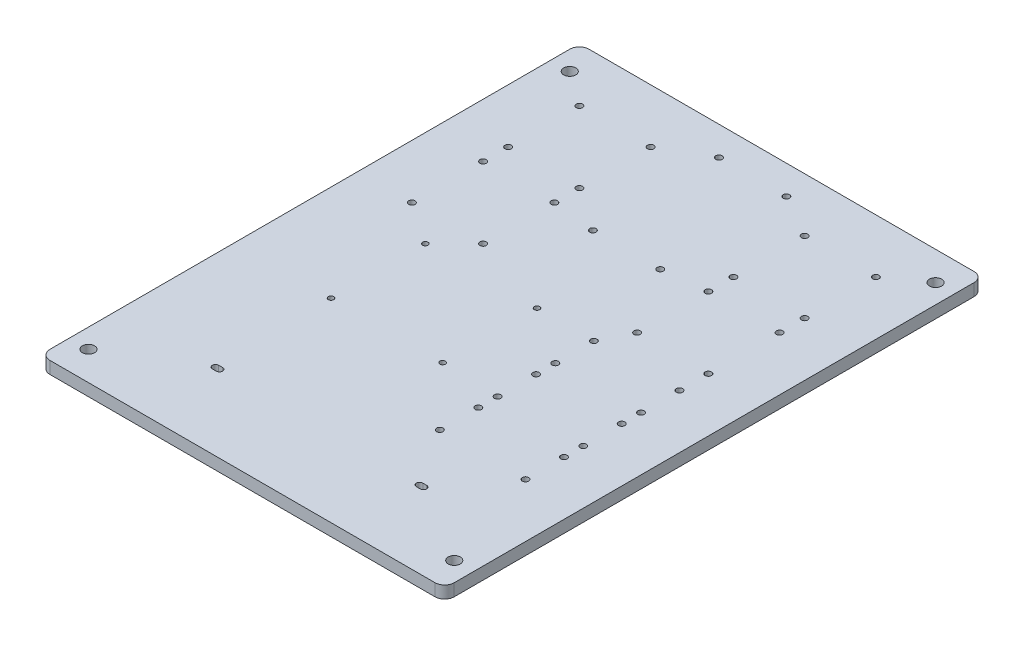
SolidWorks part; units mm, degrees
ref_plane "Front Plane" through (0, 0, 0) normal (0, 0, 1) x (1, 0, 0)
ref_plane "Top Plane" through (0, 0, 0) normal (0, 1, 0) x (1, 0, 0)
ref_plane "Right Plane" through (0, 0, 0) normal (1, 0, 0) x (0, 0, -1)
sketch "Sketch1" plane through (0, 0, 0) normal (0, 1, 0) x (1, 0, 0)
  line L1 (-105, -140) -> (105, -140)
  line L2 (-105, -140) -> (-105, 140)
  line L3 (-105, 140) -> (105, 140)
  line L4 (105, -140) -> (105, 140)
  line L5 (-105, -140) -> (105, 140) construction
  line L6 (-105, 140) -> (105, -140) construction
  point P0 (0, 0)
  dimension "D1" = 210
  dimension "D2" = 280
extrude "Boss-Extrude1" add sketch "Sketch1" against normal blind 6.35
sketch "Sketch2" plane through (0, 0, 0) normal (0, 1, 0) x (1, 0, 0)
  line L0 (-105, 140) -> (-105, -140) construction
  line L1 (95, -125) -> (-95, -125) construction
  line L2 (95, -125) -> (95, 125) construction
  line L3 (95, 125) -> (-95, 125) construction
  line L4 (-95, -125) -> (-95, 125) construction
  line L5 (95, -125) -> (-95, 125) construction
  line L6 (95, 125) -> (-95, -125) construction
  circle A0 centre (-95, 125) radius 3.15
  circle A1 centre (95, 125) radius 3.15
  circle A2 centre (-95, -125) radius 3.15
  circle A3 centre (95, -125) radius 3.15
  point P0 (0, 0)
  dimension "D1" = 6.3
  dimension "D2" = 10
  dimension "D3" = 250
extrude "Cut-Extrude1" cut sketch "Sketch2" against normal through all
sketch "Sketch3" plane through (0, 0, 0) normal (0, 1, 0) x (1, 0, 0)
  line L0 (0, 0) -> (0, -100) construction
  line L1 (0, -100) -> (53, -100) construction
  line L2 (0, -100) -> (-53, -100) construction
  line L3 (52, -100) -> (54, -100) construction
  line L4 (52, -98.35) -> (54, -98.35)
  line L5 (52, -101.65) -> (54, -101.65)
  line L6 (-54, -100) -> (-52, -100) construction
  line L7 (-54, -98.35) -> (-52, -98.35)
  line L8 (-54, -101.65) -> (-52, -101.65)
  line L9 (-105, -140) -> (105, -140) construction
  arc A0 (52, -98.35) -> (52, -101.65) centre (52, -100) ccw
  arc A1 (54, -101.65) -> (54, -98.35) centre (54, -100) ccw
  arc A2 (-54, -98.35) -> (-54, -101.65) centre (-54, -100) ccw
  arc A3 (-52, -101.65) -> (-52, -98.35) centre (-52, -100) ccw
  point P7 (53, -100)
  point P13 (-53, -100)
  dimension "D3" = 1.65
  dimension "D1" = 106
  dimension "D2" = 2
  dimension "D4" = 40
extrude "Cut-Extrude2" cut sketch "Sketch3" against normal through all
sketch "Sketch4" plane through (0, 0, 0) normal (0, 1, 0) x (1, 0, 0)
  line L0 (105, -140) -> (105, 140) construction
  line L1 (40, 75) -> (77, 75) construction
  line L2 (40, 75) -> (40, 112) construction
  line L3 (40, 112) -> (77, 112) construction
  line L4 (77, 75) -> (77, 112) construction
  line L5 (40, 75) -> (77, 112) construction
  line L6 (40, 112) -> (77, 75) construction
  line L7 (105, 140) -> (-105, 140) construction
  circle A0 centre (40, 112) radius 1.65
  circle A1 centre (77, 112) radius 1.65
  circle A2 centre (40, 75) radius 1.65
  circle A3 centre (77, 75) radius 1.65
  point P0 (58.5, 93.5)
  dimension "D1" = 3.3
  dimension "D2" = 37
  dimension "D3" = 28
  dimension "D4" = 28
extrude "Cut-Extrude3" cut sketch "Sketch4" against normal through all
pattern_linear "LPattern1" count 2 spacing 50 along (0, 0, 1) of "Cut-Extrude3"
mirror "Mirror1" about plane through (0, 0, 0) normal (1, 0, 0) of "Cut-Extrude3", "LPattern1"
sketch "Sketch5" plane through (0, 0, 0) normal (0, 1, 0) x (1, 0, 0)
  line L0 (-105, 140) -> (-105, -140) construction
  line L1 (3, -39) -> (-55, -39) construction
  line L2 (3, -39) -> (3, 10) construction
  line L3 (3, 10) -> (-55, 10) construction
  line L4 (-55, -39) -> (-55, 10) construction
  line L5 (3, -39) -> (-55, 10) construction
  line L6 (3, 10) -> (-55, -39) construction
  circle A0 centre (-77, 25) radius 1.65 construction
  circle A1 centre (-55, 10) radius 1.4
  circle A2 centre (3, 10) radius 1.4
  circle A3 centre (-55, -39) radius 1.4
  circle A4 centre (3, -39) radius 1.4
  point P0 (-26, -14.5)
  dimension "D4" = 15
  dimension "D5" = 2.8
  dimension "D1" = 58
  dimension "D2" = 49
  dimension "D3" = 50
extrude "Cut-Extrude4" cut sketch "Sketch5" against normal through all
fillet "Fillet1" radius 5 4 edges at (-105, -3.175, 140) (105, -3.175, 140) (-105, -3.175, -140) (105, -3.175, -140)
sketch "Sketch6" plane through (0, 0, 0) normal (0, 1, 0) x (1, 0, 0)
  line L0 (0, 0) -> (0, 125) construction
  line L1 (0, 125) -> (-17.5, 125) construction
  line L3 (100, 140) -> (-100, 140) construction
  line L4 (0, 125) -> (17.5, 125) construction
  line L5 (17.5, 125) -> (17.5, 59.5) construction
  line L6 (17.5, 59.5) -> (-17.5, 59.5) construction
  line L7 (-17.5, 59.5) -> (-17.5, 125) construction
  circle A0 centre (-17.5, 125) radius 1.65
  circle A1 centre (-17.5, 59.5) radius 1.65
  circle A2 centre (17.5, 59.5) radius 1.65
  circle A3 centre (17.5, 125) radius 1.65
  dimension "D3" = 3.3
  dimension "D1" = 17.5
  dimension "D2" = 15
  dimension "D4" = 65.5
extrude "Cut-Extrude5" cut sketch "Sketch6" against normal through all
sketch "Sketch7" plane through (0, 0, 0) normal (0, 1, 0) x (1, 0, 0)
  line L0 (105, -135) -> (105, 135) construction
  line L1 (77, -10) -> (32.5, -10) construction
  line L2 (77, -10) -> (77, 10) construction
  line L3 (77, 10) -> (32.5, 10) construction
  line L4 (32.5, -10) -> (32.5, 10) construction
  line L5 (77, -10) -> (32.5, 10) construction
  line L6 (77, 10) -> (32.5, -10) construction
  line L7 (3, 10) -> (32.5, 10) construction
  circle A0 centre (32.5, 10) radius 1.65
  circle A1 centre (77, 10) radius 1.65
  circle A2 centre (77, -10) radius 1.65
  circle A3 centre (32.5, -10) radius 1.65
  point P0 (54.75, 0)
  dimension "D1" = 3.3
  dimension "D2" = 20
  dimension "D3" = 44.5
  dimension "D4" = 28
extrude "Cut-Extrude6" cut sketch "Sketch7" against normal through all
pattern_linear "LPattern4" count 3 spacing 30 along (0, 0, 1) of "Cut-Extrude6"
